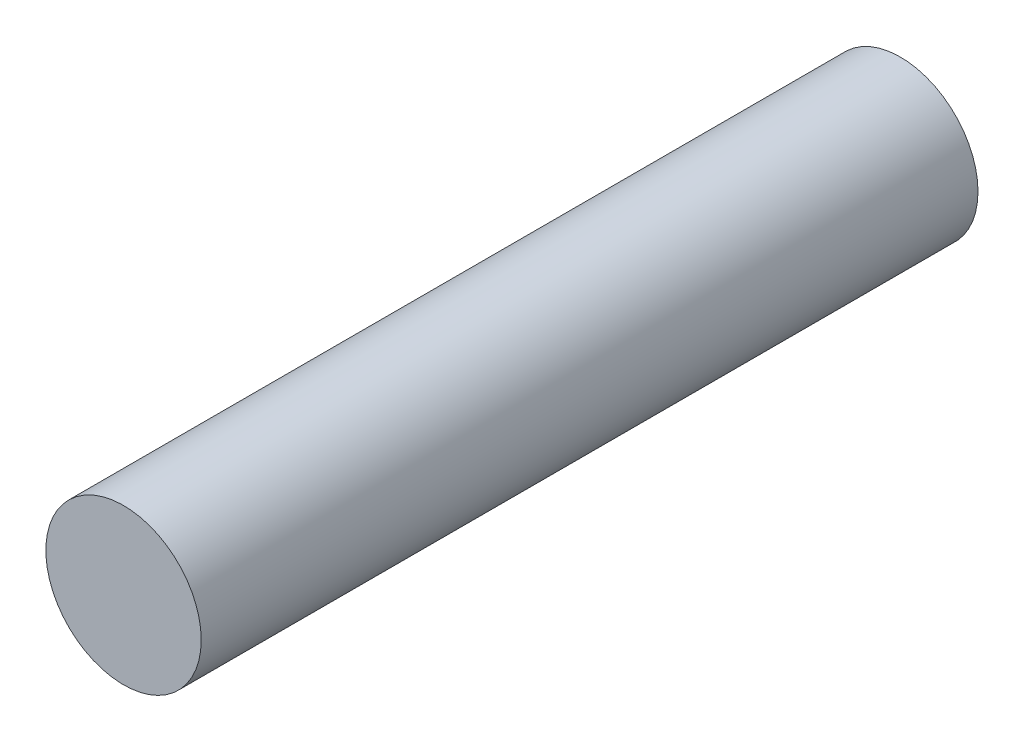
SolidWorks part; units mm, degrees
ref_plane "前视基准面" through (0, 0, 0) normal (0, 0, 1) x (1, 0, 0)
ref_plane "上视基准面" through (0, 0, 0) normal (0, 1, 0) x (1, 0, 0)
ref_plane "右视基准面" through (0, 0, 0) normal (1, 0, 0) x (0, 0, -1)
sketch "草图1" plane through (0, 0, 0) normal (0, 0, 1) x (1, 0, 0)
  circle A0 centre (0, 0) radius 6
  dimension "D1" = 12
extrude "凸台-拉伸1" add sketch "草图1" along normal blind 60
